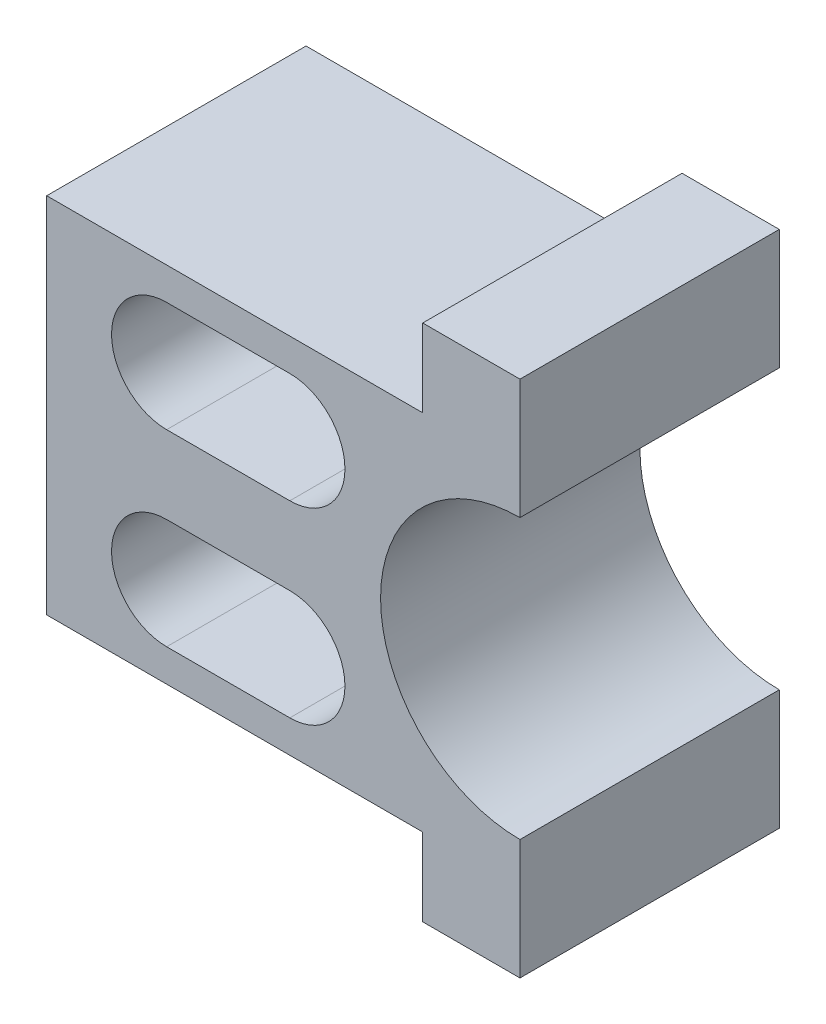
SolidWorks part; units mm, degrees
ref_plane "Спереди" through (0, 0, 0) normal (0, 0, 1) x (1, 0, 0)
ref_plane "Сверху" through (0, 0, 0) normal (0, 1, 0) x (1, 0, 0)
ref_plane "Справа" through (0, 0, 0) normal (1, 0, 0) x (0, 0, -1)
other "Configuration Table"
sketch "Эскиз1" plane through (0, 0, 0) normal (0, 0, 1) x (1, 0, 0)
  line L1 (36.5, 40) -> (-36.5, 40)
  line L2 (36.5, 40) -> (36.5, -40)
  line L3 (36.5, -40) -> (-36.5, -40)
  line L4 (-36.5, 40) -> (-36.5, -40)
  line L5 (36.5, 40) -> (-36.5, -40) construction
  line L6 (36.5, -40) -> (-36.5, 40) construction
  point P0 (0, 0)
  dimension "D1" = 80
  dimension "D2" = 73
extrude "Бобышка-Вытянуть1" add sketch "Эскиз1" along normal blind 40
sketch "Эскиз2" plane through (0, 0, 40) normal (0, 0, 1) x (1, 0, 0)
  line L0 (36.5, -40) -> (36.5, 40) construction
  line L1 (-18, -14.5) -> (1, -14.5) construction
  line L2 (-18, -6) -> (1, -6)
  line L3 (-18, -23) -> (1, -23)
  line L4 (-51.9384, 0) -> (97.7818, 0) construction
  line L5 (-18, 14.5) -> (1, 14.5) construction
  line L6 (-18, 6) -> (1, 6)
  line L7 (-18, 23) -> (1, 23)
  line L8 (-36.5, 40) -> (-36.5, -40) construction
  circle A0 centre (36.5, 0) radius 21.5
  arc A1 (-18, -6) -> (-18, -23) centre (-18, -14.5) ccw
  arc A2 (1, -23) -> (1, -6) centre (1, -14.5) ccw
  arc A3 (-18, 6) -> (-18, 23) centre (-18, 14.5) cw
  arc A4 (1, 23) -> (1, 6) centre (1, 14.5) cw
  point P6 (-8.5, -14.5)
  point P13 (-26.5, -14.5)
  point P16 (-8.5, 14.5)
  point P23 (97.7818, 0)
  point P24 (-51.9384, 0)
  dimension "D1" = 43
  dimension "D2" = 17
  dimension "D3" = 36
  dimension "D4" = 6
  dimension "D5" = 10
extrude "Вырез-Вытянуть1" cut sketch "Эскиз2" against normal through all
sketch "Эскиз3" plane through (0, 0, 40) normal (0, 0, 1) x (1, 0, 0)
  line L0 (36.5, 40) -> (-36.5, 40) construction
  line L1 (-36.5, 40) -> (21.5, 40)
  line L2 (-36.5, 40) -> (-36.5, 28)
  line L3 (-36.5, 28) -> (21.5, 28)
  line L4 (21.5, 40) -> (21.5, 28)
  line L5 (36.5, 21.5) -> (36.5, 40) construction
  line L7 (-67.3443, 0) -> (65.5875, 0) construction
  line L8 (21.5, -40) -> (21.5, -28)
  line L9 (-36.5, -40) -> (-36.5, -28)
  line L10 (-36.5, -28) -> (21.5, -28)
  line L11 (-36.5, 40) -> (-36.5, -40) construction
  dimension "D1" = 12
  dimension "D2" = 15
extrude "Вырез-Вытянуть5" cut sketch "Эскиз3" against normal through all contours L2 L3 L4 L1
mirror "Зеркальное отражение1" about plane through (0, 0, 0) normal (0, 1, 0) of "Вырез-Вытянуть5"
